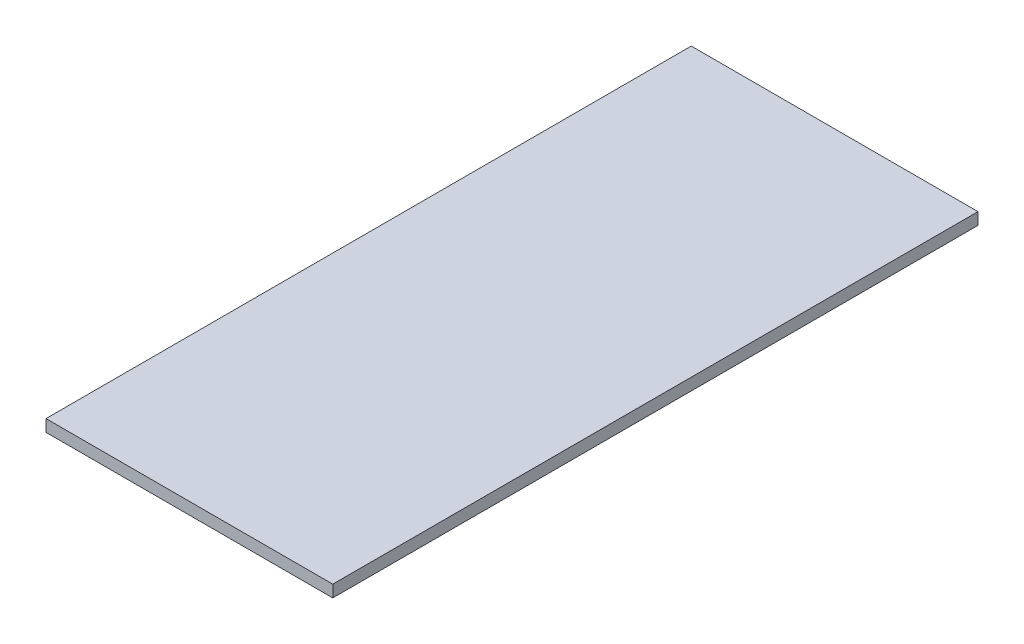
SolidWorks part; units mm, degrees
ref_plane "Front Plane" through (0, 0, 0) normal (0, 0, 1) x (1, 0, 0)
ref_plane "Top Plane" through (0, 0, 0) normal (0, 1, 0) x (1, 0, 0)
ref_plane "Right Plane" through (0, 0, 0) normal (1, 0, 0) x (0, 0, -1)
sketch "Sketch1" plane through (0, 0, 0) normal (0, 1, 0) x (1, 0, 0)
  line L1 (0, 0) -> (120, 0)
  line L2 (0, 0) -> (0, 270)
  line L3 (0, 270) -> (120, 270)
  line L4 (120, 0) -> (120, 270)
  dimension "D1" = 120
  dimension "D2" = 270
extrude "Boss-Extrude1" add sketch "Sketch1" along normal blind 5
